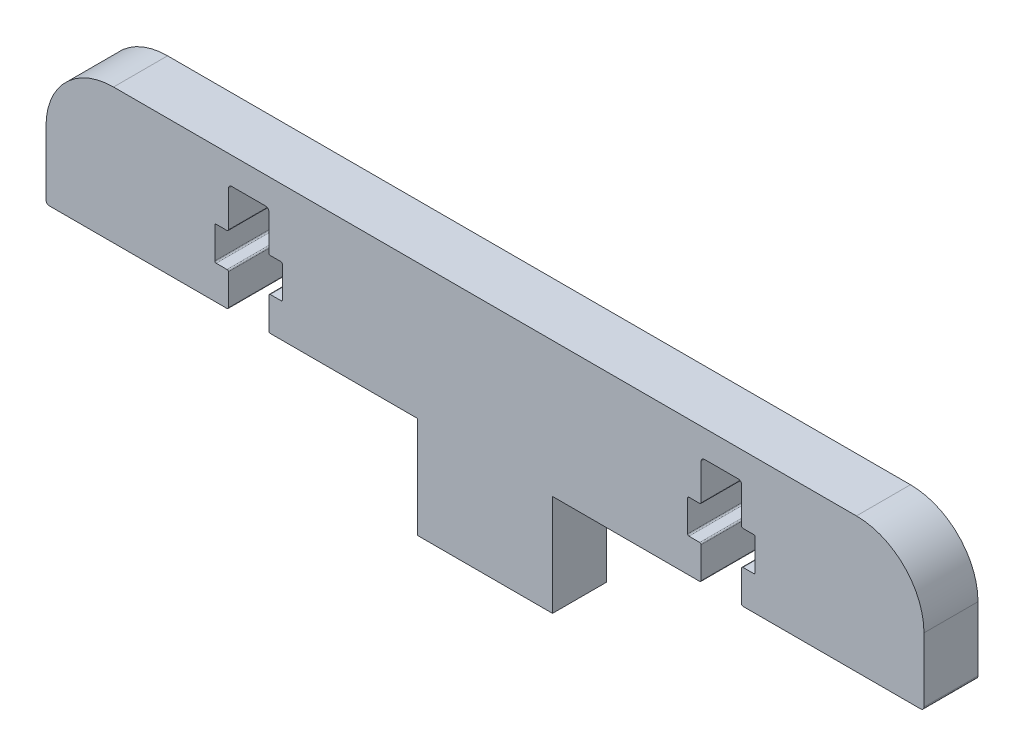
SolidWorks part; units mm, degrees
ref_plane "Front Plane" through (0, 0, 0) normal (0, 0, 1) x (1, 0, 0)
ref_plane "Top Plane" through (0, 0, 0) normal (0, 1, 0) x (1, 0, 0)
ref_plane "Right Plane" through (0, 0, 0) normal (1, 0, 0) x (0, 0, -1)
sketch "Model" plane through (0, 0, 0) normal (0, 0, 1) x (1, 0, 0)
  line L0 (-65, -10) -> (-65, -19.5)
  line L1 (-64.5, -20) -> (-38.2, -20)
  line L2 (-38, -19.8) -> (-38, -15.2)
  line L3 (-38.2, -15) -> (-39.8, -15)
  line L4 (-40, -14.8) -> (-40, -10.2)
  line L5 (-39.8, -10) -> (-38.2, -10)
  line L6 (-38, -9.8) -> (-38, -4.5)
  line L7 (-37.5, -4) -> (-32.5, -4)
  line L8 (-32, -4.5) -> (-32, -9.8)
  line L9 (-31.8, -10) -> (-30.2, -10)
  line L10 (-30, -10.2) -> (-30, -14.8)
  line L11 (-30.2, -15) -> (-31.8, -15)
  line L12 (-32, -15.2) -> (-32, -19.8)
  line L13 (-31.8, -20) -> (-10, -20)
  line L14 (-10, -20) -> (-10, -35)
  line L15 (-10, -35) -> (10, -35)
  line L16 (10, -35) -> (10, -20)
  line L17 (10, -20) -> (31.8, -20)
  line L18 (32, -19.8) -> (32, -15.2)
  line L19 (31.8, -15) -> (30.2, -15)
  line L20 (30, -14.8) -> (30, -10.2)
  line L21 (30.2, -10) -> (31.8, -10)
  line L22 (32, -9.8) -> (32, -4.5)
  line L23 (32.5, -4) -> (37.5, -4)
  line L24 (38, -4.5) -> (38, -9.8)
  line L25 (38.2, -10) -> (39.8, -10)
  line L26 (40, -10.2) -> (40, -14.8)
  line L27 (39.8, -15) -> (38.2, -15)
  line L28 (38, -15.2) -> (38, -19.8)
  line L29 (38.2, -20) -> (64.5, -20)
  line L30 (65, -19.5) -> (65, -10)
  line L31 (55, 0) -> (-55, 0)
  arc A0 (-65, -19.5) -> (-64.5, -20) centre (-64.5, -19.5) ccw
  arc A1 (-38.2, -20) -> (-38, -19.8) centre (-38.2, -19.8) ccw
  arc A2 (-38, -15.2) -> (-38.2, -15) centre (-38.2, -15.2) ccw
  arc A3 (-40, -14.8) -> (-39.8, -15) centre (-39.8, -14.8) ccw
  arc A4 (-39.8, -10) -> (-40, -10.2) centre (-39.8, -10.2) ccw
  arc A5 (-38.2, -10) -> (-38, -9.8) centre (-38.2, -9.8) ccw
  arc A6 (-37.5, -4) -> (-38, -4.5) centre (-37.5, -4.5) ccw
  arc A7 (-32, -4.5) -> (-32.5, -4) centre (-32.5, -4.5) ccw
  arc A8 (-32, -9.8) -> (-31.8, -10) centre (-31.8, -9.8) ccw
  arc A9 (-30, -10.2) -> (-30.2, -10) centre (-30.2, -10.2) ccw
  arc A10 (-30.2, -15) -> (-30, -14.8) centre (-30.2, -14.8) ccw
  arc A11 (-31.8, -15) -> (-32, -15.2) centre (-31.8, -15.2) ccw
  arc A12 (-32, -19.8) -> (-31.8, -20) centre (-31.8, -19.8) ccw
  arc A13 (31.8, -20) -> (32, -19.8) centre (31.8, -19.8) ccw
  arc A14 (32, -15.2) -> (31.8, -15) centre (31.8, -15.2) ccw
  arc A15 (30, -14.8) -> (30.2, -15) centre (30.2, -14.8) ccw
  arc A16 (30.2, -10) -> (30, -10.2) centre (30.2, -10.2) ccw
  arc A17 (31.8, -10) -> (32, -9.8) centre (31.8, -9.8) ccw
  arc A18 (32.5, -4) -> (32, -4.5) centre (32.5, -4.5) ccw
  arc A19 (38, -4.5) -> (37.5, -4) centre (37.5, -4.5) ccw
  arc A20 (38, -9.8) -> (38.2, -10) centre (38.2, -9.8) ccw
  arc A21 (40, -10.2) -> (39.8, -10) centre (39.8, -10.2) ccw
  arc A22 (39.8, -15) -> (40, -14.8) centre (39.8, -14.8) ccw
  arc A23 (38.2, -15) -> (38, -15.2) centre (38.2, -15.2) ccw
  arc A24 (38, -19.8) -> (38.2, -20) centre (38.2, -19.8) ccw
  arc A25 (64.5, -20) -> (65, -19.5) centre (64.5, -19.5) ccw
  arc A26 (65, -10) -> (55, 0) centre (55, -10) ccw
  arc A27 (-55, 0) -> (-65, -10) centre (-55, -10) ccw
extrude "Boss-Extrude1" add sketch "Model" along normal blind 8
